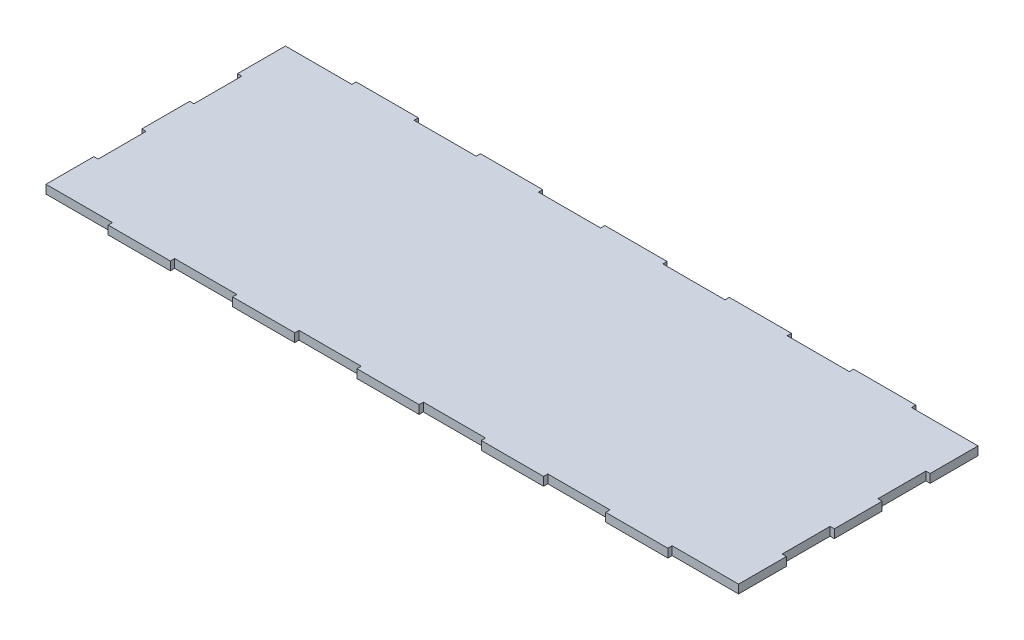
SolidWorks part; units mm, degrees
ref_plane "Front Plane" through (0, 0, 0) normal (0, 0, 1) x (1, 0, 0)
ref_plane "Top Plane" through (0, 0, 0) normal (0, 1, 0) x (1, 0, 0)
ref_plane "Right Plane" through (0, 0, 0) normal (1, 0, 0) x (0, 0, -1)
sketch "Sketch1" plane through (0, 0, 0) normal (0, 1, 0) x (1, 0, 0)
  line L0 (0, 0) -> (508, 0)
  line L1 (508, 0) -> (508, 177.8)
  line L2 (508, 177.8) -> (0, 177.8)
  line L3 (0, 177.8) -> (0, 0)
  line L4 (0, 0) -> (0, -3.175)
  line L5 (0, -3.175) -> (46.1818, -3.175)
  line L6 (46.1818, -3.175) -> (46.1818, 0)
  line L7 (46.1818, 0) -> (0, 0)
  line L8 (46.1818, 0) -> (46.1818, -3.175)
  line L9 (46.1818, -3.175) -> (92.3636, -3.175)
  line L10 (92.3636, -3.175) -> (92.3636, 0)
  line L11 (92.3636, 0) -> (46.1818, 0)
  line L12 (92.3636, 0) -> (92.3636, -3.175)
  line L13 (92.3636, -3.175) -> (138.5455, -3.175)
  line L14 (138.5455, -3.175) -> (138.5455, 0)
  line L15 (138.5455, 0) -> (92.3636, 0)
  line L16 (138.5455, 0) -> (138.5455, -3.175)
  line L17 (138.5455, -3.175) -> (184.7273, -3.175)
  line L18 (184.7273, -3.175) -> (184.7273, 0)
  line L19 (184.7273, 0) -> (138.5455, 0)
  line L20 (184.7273, 0) -> (184.7273, -3.175)
  line L21 (184.7273, -3.175) -> (230.9091, -3.175)
  line L22 (230.9091, -3.175) -> (230.9091, 0)
  line L23 (230.9091, 0) -> (184.7273, 0)
  line L24 (230.9091, 0) -> (230.9091, -3.175)
  line L25 (230.9091, -3.175) -> (277.0909, -3.175)
  line L26 (277.0909, -3.175) -> (277.0909, 0)
  line L27 (277.0909, 0) -> (230.9091, 0)
  line L28 (277.0909, 0) -> (277.0909, -3.175)
  line L29 (277.0909, -3.175) -> (323.2727, -3.175)
  line L30 (323.2727, -3.175) -> (323.2727, 0)
  line L31 (323.2727, 0) -> (277.0909, 0)
  line L32 (323.2727, 0) -> (323.2727, -3.175)
  line L33 (323.2727, -3.175) -> (369.4545, -3.175)
  line L34 (369.4545, -3.175) -> (369.4545, 0)
  line L35 (369.4545, 0) -> (323.2727, 0)
  line L36 (369.4545, 0) -> (369.4545, -3.175)
  line L37 (369.4545, -3.175) -> (415.6364, -3.175)
  line L38 (415.6364, -3.175) -> (415.6364, 0)
  line L39 (415.6364, 0) -> (369.4545, 0)
  line L40 (415.6364, 0) -> (415.6364, -3.175)
  line L41 (415.6364, -3.175) -> (461.8182, -3.175)
  line L42 (461.8182, -3.175) -> (461.8182, 0)
  line L43 (461.8182, 0) -> (415.6364, 0)
  line L44 (461.8182, 0) -> (461.8182, -3.175)
  line L45 (461.8182, -3.175) -> (508, -3.175)
  line L46 (508, -3.175) -> (508, 0)
  line L47 (508, 0) -> (461.8182, 0)
  line L48 (0, 0) -> (46.1818, 0) construction
  line L49 (0, 177.8) -> (-3.175, 177.8)
  line L50 (-3.175, 177.8) -> (-3.175, 142.24)
  line L51 (-3.175, 142.24) -> (0, 142.24)
  line L52 (0, 142.24) -> (0, 177.8)
  line L53 (0, 142.24) -> (-3.175, 142.24)
  line L54 (-3.175, 142.24) -> (-3.175, 106.68)
  line L55 (-3.175, 106.68) -> (0, 106.68)
  line L56 (0, 106.68) -> (0, 142.24)
  line L57 (0, 106.68) -> (-3.175, 106.68)
  line L58 (-3.175, 106.68) -> (-3.175, 71.12)
  line L59 (-3.175, 71.12) -> (0, 71.12)
  line L60 (0, 71.12) -> (0, 106.68)
  line L61 (0, 71.12) -> (-3.175, 71.12)
  line L62 (-3.175, 71.12) -> (-3.175, 35.56)
  line L63 (-3.175, 35.56) -> (0, 35.56)
  line L64 (0, 35.56) -> (0, 71.12)
  line L65 (0, 35.56) -> (-3.175, 35.56)
  line L66 (-3.175, 35.56) -> (-3.175, 0)
  line L67 (-3.175, 0) -> (0, 0)
  line L68 (0, 0) -> (0, 35.56)
  line L69 (0, 177.8) -> (0, 142.24) construction
  line L70 (0, 88.9) -> (508, 88.9) construction
  line L71 (254, 177.8) -> (254, 0) construction
  line L72 (461.8182, 177.8) -> (415.6364, 177.8)
  line L73 (461.8182, 180.975) -> (461.8182, 177.8)
  line L74 (415.6364, 180.975) -> (461.8182, 180.975)
  line L75 (415.6364, 177.8) -> (415.6364, 180.975)
  line L76 (369.4545, 177.8) -> (323.2727, 177.8)
  line L77 (369.4545, 180.975) -> (369.4545, 177.8)
  line L78 (323.2727, 180.975) -> (369.4545, 180.975)
  line L79 (323.2727, 177.8) -> (323.2727, 180.975)
  line L80 (277.0909, 177.8) -> (230.9091, 177.8)
  line L81 (277.0909, 180.975) -> (277.0909, 177.8)
  line L82 (230.9091, 180.975) -> (277.0909, 180.975)
  line L83 (230.9091, 177.8) -> (230.9091, 180.975)
  line L84 (184.7273, 177.8) -> (138.5455, 177.8)
  line L85 (184.7273, 180.975) -> (184.7273, 177.8)
  line L86 (138.5455, 180.975) -> (184.7273, 180.975)
  line L87 (138.5455, 177.8) -> (138.5455, 180.975)
  line L88 (92.3636, 177.8) -> (46.1818, 177.8)
  line L89 (92.3636, 180.975) -> (92.3636, 177.8)
  line L90 (46.1818, 180.975) -> (92.3636, 180.975)
  line L91 (46.1818, 177.8) -> (46.1818, 180.975)
  line L92 (508, 0) -> (508, 35.56)
  line L93 (511.175, 0) -> (508, 0)
  line L94 (511.175, 35.56) -> (511.175, 0)
  line L95 (508, 35.56) -> (511.175, 35.56)
  line L96 (508, 71.12) -> (508, 106.68)
  line L97 (511.175, 71.12) -> (508, 71.12)
  line L98 (511.175, 106.68) -> (511.175, 71.12)
  line L99 (508, 106.68) -> (511.175, 106.68)
  line L100 (508, 142.24) -> (508, 177.8)
  line L101 (511.175, 142.24) -> (508, 142.24)
  line L102 (511.175, 177.8) -> (511.175, 142.24)
  line L103 (508, 177.8) -> (511.175, 177.8)
  point P105 (230.9089, 1126.0048)
  dimension "D1" = 508
  dimension "D2" = 177.8
  dimension "D3" = 3.175
  dimension "D4" = 46.1818
  dimension "D6" = 46.1818
  dimension "D7" = 3.175
  dimension "D9" = 35.56
  dimension "D10" = 35.56
  dimension "D5" = 11
  dimension "D8" = 5
extrude "Boss-Extrude1" add sketch "Sketch1" along normal blind 6.35 contours L2 L3 L0 L1 | L75 L2 L73 L74 | L79 L2 L77 L78 | L83 L2 L81 L82 | L87 L2 L85 L86 | L91 L2 L89 L90 | L50 L51 L3 L49 | L58 L59 L3 L55 | L66 L67 L3 L63 | L33 L34 L0 L30 | L41 L42 L0 L38 | L95 L1 L93 L94 | L99 L1 L97 L98 | L103 L1 L101 L102 | L9 L10 L11 L8 | L17 L18 L19 L16 | L25 L26 L27 L24
equation "\"Height\"= 12in"
equation "\"Depth\"= 7in"
equation "\"WallThickness\"= 0.125in"
equation "\"FloorThickness\"= 0.25in"
equation "\"Width\" = 30in"
equation "\"D7@Sketch1\"=\"WallThickness\""
equation "\"D1@Boss-Extrude1\"=\"FloorThickness\""
